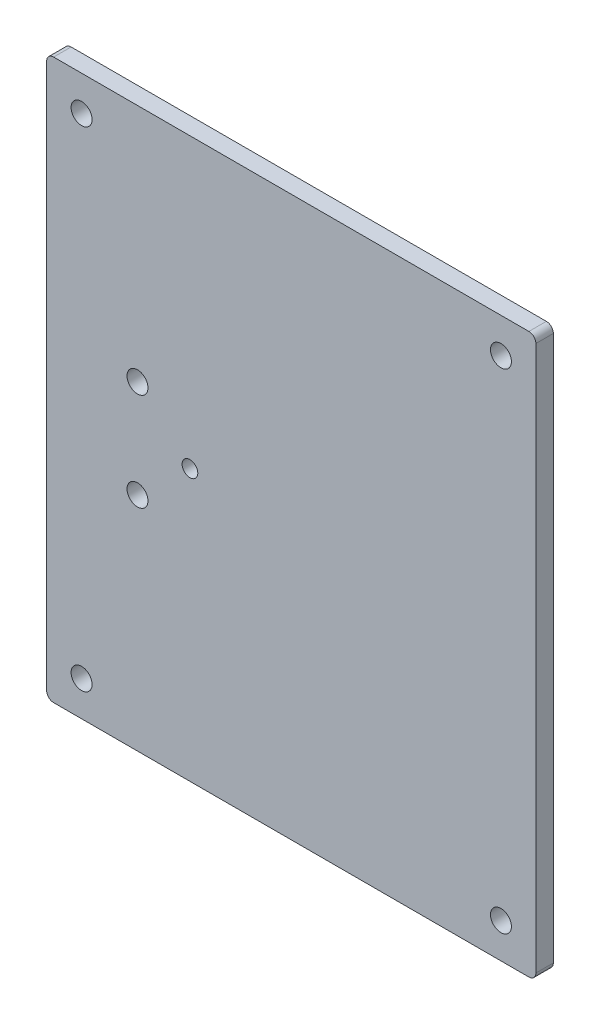
SolidWorks part; units mm, degrees
ref_plane "Front Plane" through (0, 0, 0) normal (0, 0, 1) x (1, 0, 0)
ref_plane "Top Plane" through (0, 0, 0) normal (0, 1, 0) x (1, 0, 0)
ref_plane "Right Plane" through (0, 0, 0) normal (1, 0, 0) x (0, 0, -1)
sketch "Model" plane through (0, 0, 0) normal (0, 0, 1) x (1, 0, 0)
  line L0 (0, 0) -> (0, 160)
  line L1 (0, 160) -> (140, 160)
  line L2 (140, 160) -> (140, 0)
  line L3 (140, 0) -> (0, 0)
  circle A0 centre (26, 91.5) radius 3
  circle A2 centre (10, 150) radius 3
  circle A3 centre (130, 10) radius 3
  circle A4 centre (10, 10) radius 3
  circle A5 centre (130, 150) radius 3
  circle A7 centre (26, 63.5) radius 3
  circle A8 centre (41, 77.5) radius 2.25
  dimension "D1" = 140
  dimension "D3" = 10
  dimension "D4" = 10
  dimension "D5" = 10
  dimension "D6" = 10
  dimension "D7" = 28
  dimension "D8" = 6
  dimension "D9" = 6
  dimension "D10" = 26
  dimension "D11" = 68.5
  dimension "D12" = 4.5
  dimension "D13" = 41
  dimension "D14" = 82.5
  dimension "D2" = 160
extrude "Boss-Extrude1" add sketch "Model" along normal blind 5
fillet "Fillet1" radius 2 4 edges at (0, 0, 2.5) (140, 0, 2.5) (0, 160, 2.5) (140, 160, 2.5)
